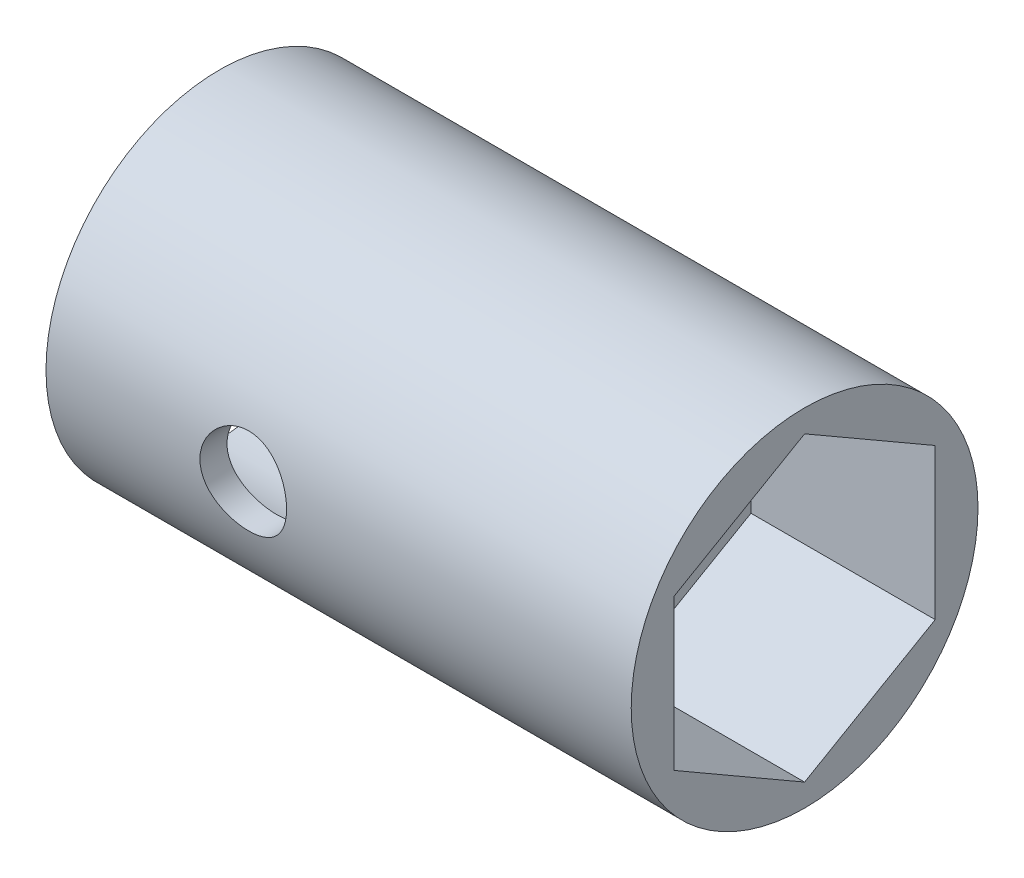
SolidWorks part; units mm, degrees
ref_plane "Alzado" through (0, 0, 0) normal (0, 0, 1) x (1, 0, 0)
ref_plane "Planta" through (0, 0, 0) normal (0, 1, 0) x (1, 0, 0)
ref_plane "Vista lateral" through (0, 0, 0) normal (1, 0, 0) x (0, 0, -1)
sketch "Croquis1" plane through (0, 0, 0) normal (1, 0, 0) x (0, 0, -1)
  line L1 (0, -6.9282) -> (6, -3.4641) construction
  line L2 (6, -3.4641) -> (6, 3.4641) construction
  line L3 (6, 3.4641) -> (0, 6.9282) construction
  line L4 (0, 6.9282) -> (-6, 3.4641) construction
  line L5 (-6, 3.4641) -> (-6, -3.4641) construction
  line L6 (-6, -3.4641) -> (0, -6.9282) construction
  circle A0 centre (0, 0) radius 6.4 construction
  circle A1 centre (0, 0) radius 6 construction
  circle A2 centre (0, 0) radius 8
  point P11 (0, 0)
  dimension "D2" = 12.8
  dimension "D3" = 16
  dimension "D1" = 12
extrude "Saliente-Extruir1" add sketch "Croquis1" along normal blind 20
sketch "Croquis2" plane through (20, 0, 0) normal (1, 0, 0) x (0, 0, -1)
  line L1 (0, -6.9571) -> (6.025, -3.4785)
  line L2 (6.025, -3.4785) -> (6.025, 3.4785)
  line L3 (6.025, 3.4785) -> (0, 6.9571)
  line L4 (0, 6.9571) -> (-6.025, 3.4785)
  line L5 (-6.025, 3.4785) -> (-6.025, -3.4785)
  line L6 (-6.025, -3.4785) -> (0, -6.9571)
  circle A0 centre (0, 0) radius 6.025 construction
  dimension "D1" = 12.05
extrude "Cortar-Extruir1" cut sketch "Croquis2" against normal blind 8.5
sketch "Croquis3" plane through (0, 0, 0) normal (-1, 0, 0) x (0, 0, 1)
  circle A0 centre (0, 0) radius 6.75
  dimension "D1" = 13.5
extrude "Cortar-Extruir2" cut sketch "Croquis3" against normal blind 9
sketch "Croquis4" plane through (9, 0, 0) normal (-1, 0, 0) x (0, 0, 1)
  circle A0 centre (0, 0) radius 2.025
  dimension "D1" = 4.05
extrude "Cortar-Extruir3" cut sketch "Croquis4" against normal up to next
sketch "Croquis5" plane through (0, 0, 0) normal (0, 0, 1) x (1, 0, 0)
  circle A0 centre (2.1, 0) radius 2
  dimension "D1" = 4
  dimension "D2" = 2.1
extrude "Cortar-Extruir4" cut sketch "Croquis5" against normal through all and the other way blind 9
sketch "Croquis6" plane through (0, 0, 0) normal (-1, 0, 0) x (0, 0, 1)
  circle A0 centre (0, 0) radius 6.75 construction
  circle A1 centre (0, 0) radius 8
  circle A2 centre (0, 0) radius 8
  circle A3 centre (0, 0) radius 6.75
  dimension "D1" = 0
extrude "Saliente-Extruir2" add sketch "Croquis6" along normal blind 7
equation "\"D1@Croquis2\"=12+0.05"
equation "\"D1@Croquis3\"=12.8+0.7"
